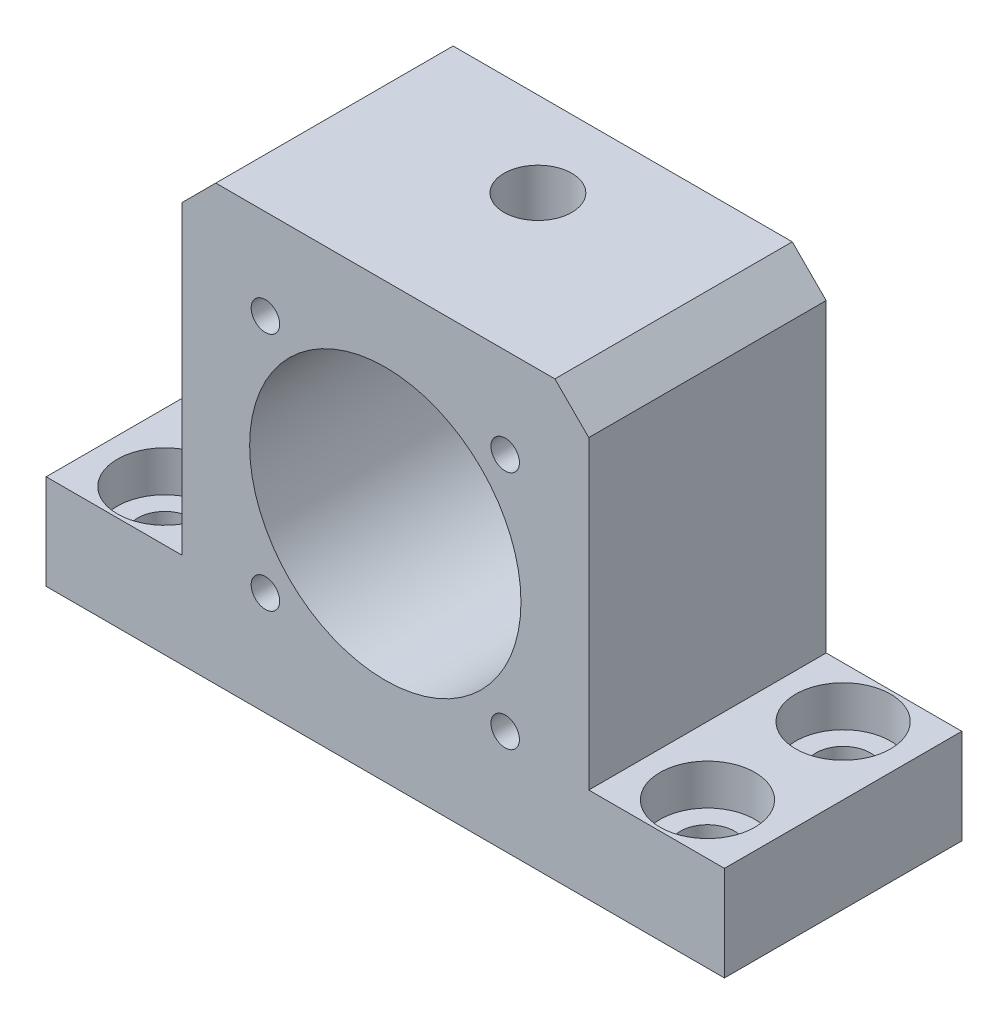
SolidWorks part; units mm, degrees
ref_plane "前视基准面" through (0, 0, 0) normal (0, 0, 1) x (1, 0, 0)
ref_plane "上视基准面" through (0, 0, 0) normal (0, 1, 0) x (1, 0, 0)
ref_plane "右视基准面" through (0, 0, 0) normal (1, 0, 0) x (0, 0, -1)
sketch "草图1" plane through (0, 0, 0) normal (0, 0, 1) x (1, 0, 0)
  line L0 (30, 14) -> (50, 14)
  line L1 (-50, 0) -> (50, 0)
  line L2 (-50, 0) -> (-50, 14)
  line L3 (-50, 14) -> (-30, 14)
  line L4 (50, 0) -> (50, 14)
  line L5 (-30, 59) -> (-25, 64)
  line L6 (-30, 14) -> (-30, 59)
  line L7 (-25, 64) -> (25, 64)
  line L8 (30, 14) -> (30, 59)
  line L9 (25, 64) -> (30, 59)
  circle A0 centre (0, 33) radius 20
  point P5 (30, 64)
  point P6 (-30, 64)
  point P10 (0, 0)
  dimension "D5" = 40
  dimension "D6" = 33
  dimension "D1" = 100
  dimension "D2" = 60
  dimension "D3" = 64
  dimension "D4" = 50
extrude "拉伸1" add sketch "草图1" along normal mid plane 35
hole_wizard "M6 六角凹头螺钉的柱形沉头孔1" positions "3D草图1" profile "草图2" counterbore size "M6" standard "ISO" end condition through all
sketch3d "3D草图1"
  point P0 (-40, 14, 10)
  point P2 (-40, 14, -10)
  point P4 (40, 14, -10)
  point P6 (40, 14, 10)
sketch "草图2" plane through (-40, 14, 10) normal (1, 0, 0) x (0, 0, 1)
  line L0 (0, 0) -> (0, 14)
  line L1 (0, 14) -> (4, 14)
  line L3 (4, 14) -> (4, 6)
  line L4 (4, 6) -> (7, 6)
  line L5 (7, 6) -> (7, 0)
  line L7 (7, 0) -> (0, 0)
  line L11 (0, -6.35) -> (0, 107.95) construction
  dimension "通孔孔直径" = 8
  dimension "通孔孔深度" = 14
  dimension "柱形沉头孔直径" = 14
  dimension "柱形沉头孔深度" = 6
hole_wizard "M5 螺纹孔1" positions "3D草图3" profile "草图4" tap size "M5" standard "GB"
sketch3d "3D草图3"
  circle A0 centre (-17.6777, 15.3223, 30.5) radius 5 construction
  circle A1 centre (-17.6777, 15.3223, 30.5) radius 5
  circle A2 centre (17.6777, 50.6777, 30.5) radius 5 construction
  circle A3 centre (17.6777, 50.6777, 30.5) radius 5
  circle A4 centre (17.6777, 15.3223, 30.5) radius 5 construction
  circle A5 centre (17.6777, 15.3223, 30.5) radius 5
  circle A6 centre (-17.6777, 50.6777, 30.5) radius 5 construction
  circle A7 centre (-17.6777, 50.6777, 30.5) radius 5
  point P0 (-17.6777, 15.3223, 17.5)
  point P2 (17.6777, 15.3223, 17.5)
  point P4 (17.6777, 50.6777, 17.5)
  point P6 (-17.6777, 50.6777, 17.5)
  point P11 (-17.6777, 15.3223, 35.5)
  point P13 (-17.6777, 15.3223, 35.5)
  point P16 (17.6777, 50.6777, 35.5)
  point P18 (17.6777, 50.6777, 35.5)
  point P21 (17.6777, 15.3223, 35.5)
  point P23 (17.6777, 15.3223, 35.5)
  point P26 (-17.6777, 50.6777, 35.5)
  point P28 (-17.6777, 50.6777, 35.5)
sketch "草图4" plane through (-17.6777, 15.3223, 17.5) normal (1, 0, 0) x (0, -1, 0)
  line L0 (0, 0) -> (0, 13.6618)
  line L1 (0, 13.6618) -> (2.1, 12.4)
  line L2 (2.1, 12.4) -> (2.1, 0)
  line L5 (2.1, 0) -> (0, 0)
  line L10 (0, 13.6618) -> (-2.1, 12.4) construction
  line L11 (0, -6.35) -> (0, 107.95) construction
  dimension "螺纹孔钻头直径" = 4.2
  dimension "螺纹孔钻头深度" = 12.4
  dimension "导头角度" = 118
cosmetic thread "孔螺蚊线1" parameters "D1"=10, "D2"=5
cosmetic thread "孔螺蚊线2" parameters "D1"=10, "D2"=5
cosmetic thread "孔螺蚊线3" parameters "D1"=10, "D2"=5
cosmetic thread "孔螺蚊线4" parameters "D1"=10, "D2"=5
sketch "草图5" plane through (0, 64, 0) normal (0, 1, 0) x (1, 0, 0)
  circle A0 centre (0, 5) radius 5
  dimension "D1" = 10
  dimension "D2" = 5
extrude "拉伸2" cut sketch "草图5" against normal up to next
